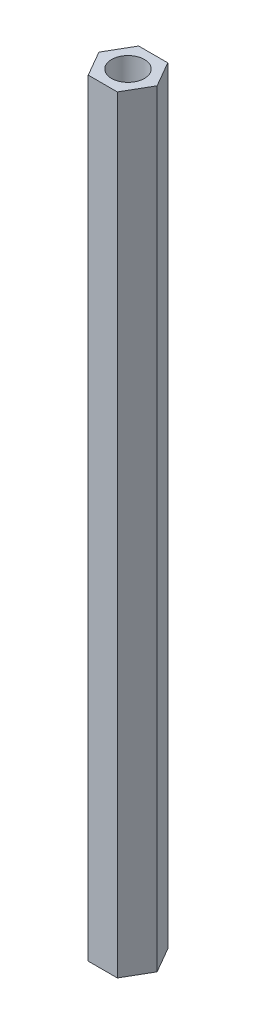
SolidWorks part; units mm, degrees
ref_plane "Front Plane" through (0, 0, 0) normal (0, 0, 1) x (1, 0, 0)
ref_plane "Top Plane" through (0, 0, 0) normal (0, 1, 0) x (1, 0, 0)
ref_plane "Right Plane" through (0, 0, 0) normal (1, 0, 0) x (0, 0, -1)
sketch "Sketch1" plane through (0, 0, 0) normal (0, 1, 0) x (1, 0, 0)
  line L1 (2.6558, 0) -> (1.3279, 2.3)
  line L2 (1.3279, 2.3) -> (-1.3279, 2.3)
  line L3 (-1.3279, 2.3) -> (-2.6558, 0)
  line L4 (-2.6558, 0) -> (-1.3279, -2.3)
  line L5 (-1.3279, -2.3) -> (1.3279, -2.3)
  line L6 (1.3279, -2.3) -> (2.6558, 0)
  circle A0 centre (0, 0) radius 1.5
  circle A1 centre (0, 0) radius 2.3 construction
  dimension "D1" = 3
  dimension "D2" = 4.6
extrude "Boss-Extrude1" add sketch "Sketch1" along normal blind 70
